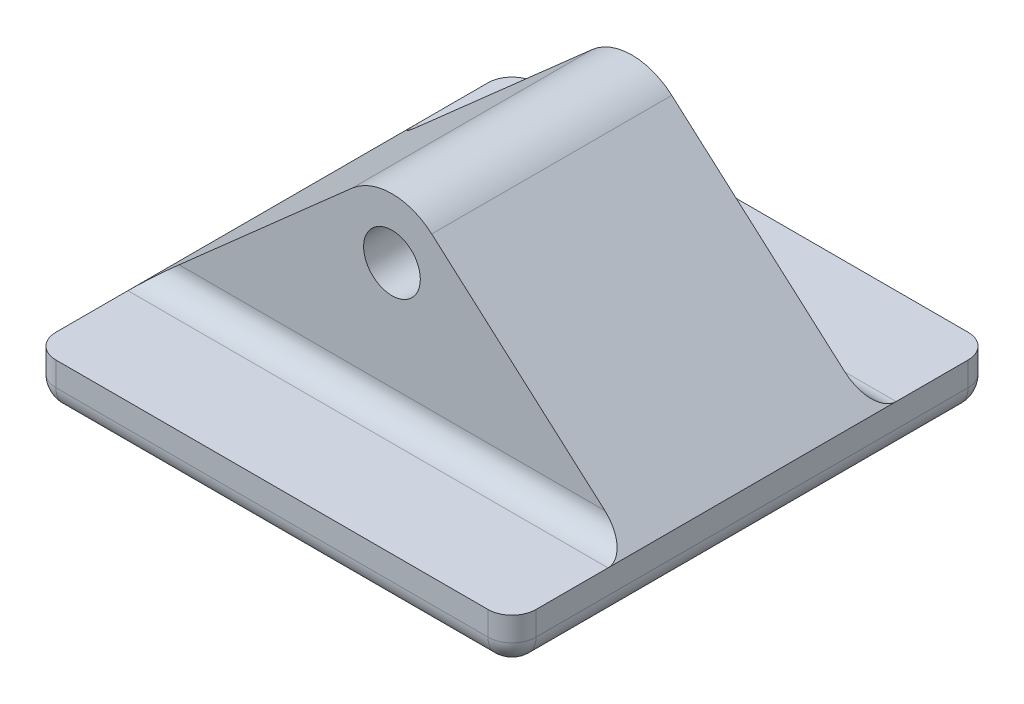
SolidWorks part; units mm, degrees
ref_plane "Front Plane" through (0, 0, 0) normal (0, 0, 1) x (1, 0, 0)
ref_plane "Top Plane" through (0, 0, 0) normal (0, 1, 0) x (1, 0, 0)
ref_plane "Right Plane" through (0, 0, 0) normal (1, 0, 0) x (0, 0, -1)
sketch "Sketch1" plane through (0, 0, 0) normal (0, 1, 0) x (1, 0, 0)
  line L1 (-12.7, -12.7) -> (12.7, -12.7)
  line L2 (-12.7, -12.7) -> (-12.7, 12.7)
  line L3 (-12.7, 12.7) -> (12.7, 12.7)
  line L4 (12.7, -12.7) -> (12.7, 12.7)
  line L5 (-12.7, -12.7) -> (12.7, 12.7) construction
  line L6 (-12.7, 12.7) -> (12.7, -12.7) construction
  point P0 (0, 0)
  dimension "D1" = 25.4
extrude "Boss-Extrude1" add sketch "Sketch1" along normal blind 2.54
sketch "Sketch2" plane through (0, 2.54, 0) normal (0, 1, 0) x (1, 0, 0)
  line L0 (12.7, -12.7) -> (12.7, 12.7) construction
  line L1 (-12.7, 6.35) -> (12.7, 6.35)
  line L2 (-12.7, 6.35) -> (-12.7, -6.35)
  line L3 (-12.7, -6.35) -> (12.7, -6.35)
  line L4 (12.7, 6.35) -> (12.7, -6.35)
  line L5 (-12.7, 6.35) -> (12.7, -6.35) construction
  line L6 (-12.7, -6.35) -> (12.7, 6.35) construction
  point P0 (0, 0)
  dimension "D1" = 12.7
extrude "Boss-Extrude2" add sketch "Sketch2" along normal blind 12.7
sketch "Sketch3" plane through (0, 0, 6.35) normal (0, 0, 1) x (1, 0, 0)
  line L0 (-12.7, 2.54) -> (-2.1023, 11.9042)
  line L1 (2.1023, 11.9042) -> (12.7, 2.54)
  line L3 (-12.7, 2.54) -> (12.7, 2.54)
  line L4 (-12.7, 2.54) -> (-12.7, 15.24)
  line L5 (-12.7, 15.24) -> (12.7, 15.24)
  line L6 (12.7, 2.54) -> (12.7, 15.24)
  circle A0 centre (0, 9.525) radius 1.5
  arc A1 (-2.1023, 11.9042) -> (2.1023, 11.9042) centre (0, 9.525) cw
  line M2 (12.7, 2.54) -> (12.7, 15.24)
  line M3 (12.7, 15.24) -> (-12.7, 15.24)
  line M4 (-12.7, 15.24) -> (-12.7, 2.54)
  dimension "D1" = 3
  dimension "D3" = 3.175
  dimension "D2" = 9.525
extrude "Cut-Extrude1" cut sketch "Sketch3" against normal through all contours L0 A1 L1 M2 M3 M4 | A0
fillet "Fillet1" radius 1.27 10 edges at (0, 0, -12.7) (-12.7, 0, 0) (0, 0, 12.7) (12.7, 0, 0) (-12.7, 1.27, 12.7) (12.7, 1.27, 12.7) (-12.7, 1.27, -12.7) (12.7, 1.27, -12.7)
